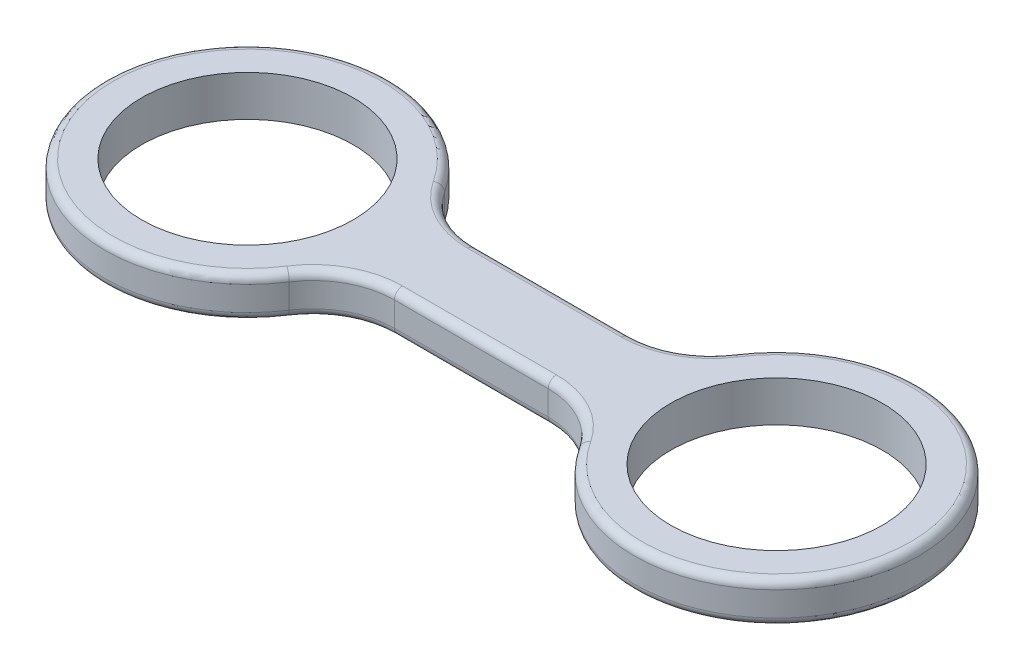
SolidWorks part; units mm, degrees
ref_plane "Front Plane" through (0, 0, 0) normal (0, 0, 1) x (1, 0, 0)
ref_plane "Top Plane" through (0, 0, 0) normal (0, 1, 0) x (1, 0, 0)
ref_plane "Right Plane" through (0, 0, 0) normal (1, 0, 0) x (0, 0, -1)
sketch "Sketch1" plane through (0, 0, 0) normal (0, 1, 0) x (1, 0, 0)
  line L0 (0, 0) -> (65, 0) construction
  line L1 (16.7705, 5) -> (48.2295, 5)
  line L2 (16.7705, -5) -> (48.2295, -5)
  circle A0 centre (0, 0) radius 13
  circle A1 centre (65, 0) radius 13
  arc A2 (16.7705, 5) -> (16.7705, -5) centre (0, 0) ccw
  arc A3 (48.2295, -5) -> (48.2295, 5) centre (65, 0) ccw
  dimension "D2" = 26
  dimension "D3" = 26
  dimension "D4" = 35
  dimension "D5" = 35
  dimension "D1" = 65
  dimension "D6" = 5
  dimension "D7" = 5
extrude "Boss-Extrude1" add sketch "Sketch1" along normal blind 5
fillet "Fillet1" radius 10 4 edges at (48.2295, 2.5, 5) (16.7705, 2.5, 5) (48.2295, 2.5, -5) (16.7705, 2.5, -5)
fillet "Fillet2" radius 1 16 edges at (18.2815, 5, -6.2095) (32.5, 5, -5) (46.7185, 5, -6.2095) (82.5, 5, 0) (46.7185, 5, 6.2095) (32.5, 5, 5) (18.2815, 5, 6.2095) (18.2815, 0, 6.2095) (32.5, 0, 5) (46.7185, 0, 6.2095) (82.5, 0, 0) (46.7185, 0, -6.2095) (32.5, 0, -5) (18.2815, 0, -6.2095) (-17.5, 0, 0) (-17.5, 5, 0)
